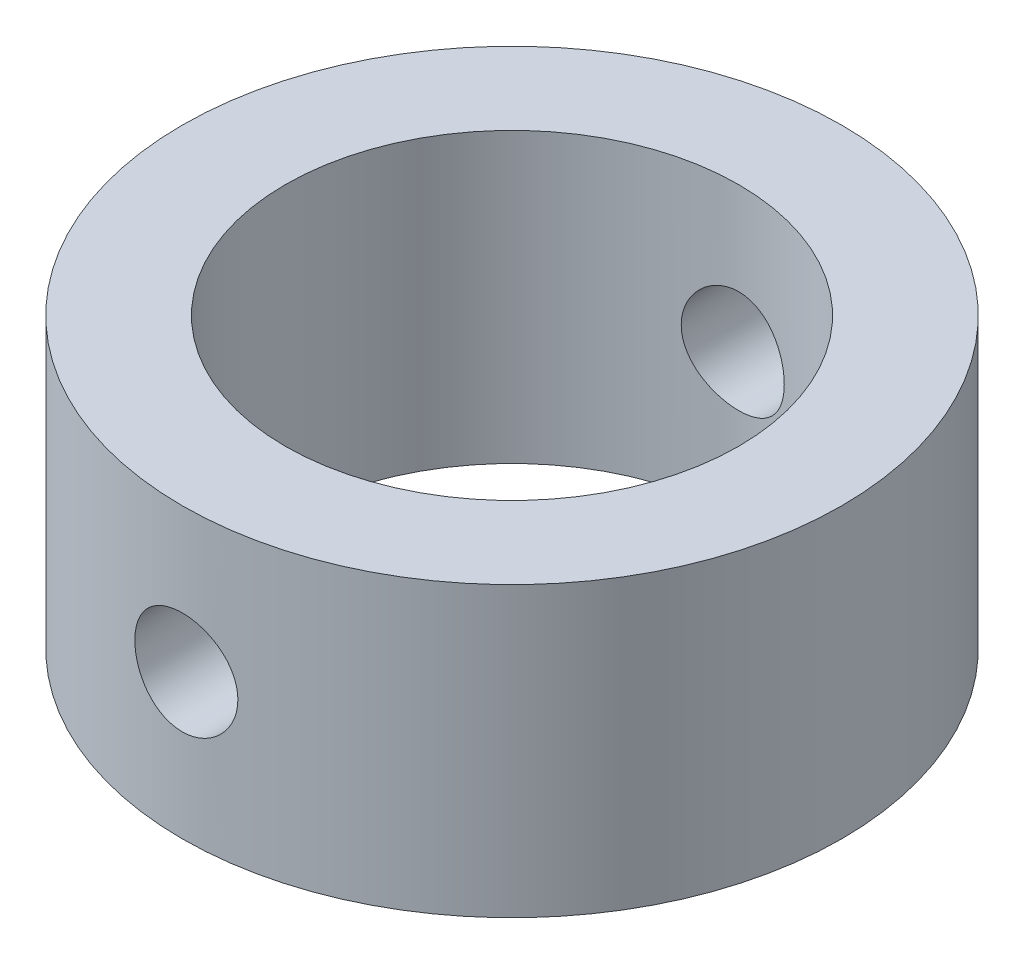
SolidWorks part; units mm, degrees
ref_plane "Front Plane" through (0, 0, 0) normal (0, 0, 1) x (1, 0, 0)
ref_plane "Top Plane" through (0, 0, 0) normal (0, 1, 0) x (1, 0, 0)
ref_plane "Right Plane" through (0, 0, 0) normal (1, 0, 0) x (0, 0, -1)
sketch "Sketch1" plane through (0, 0, 0) normal (0, 0, 1) x (1, 0, 0)
  line L0 (0, 0) -> (0, 14) construction
  line L2 (-16, 14) -> (-11, 14)
  line L3 (-16, 14) -> (-16, 0)
  line L4 (-16, 0) -> (-11, 0)
  line L5 (-11, 14) -> (-11, 0)
  dimension "D1" = 14
  dimension "D2" = 22
  dimension "D3" = 32
revolve "Revolve1" add sketch "Sketch1" angle 360 about L0
sketch "Sketch2" plane through (0, 0, 0) normal (0, 0, 1) x (1, 0, 0)
  line L0 (-16, 0) -> (16, 0) construction
  circle A0 centre (0, 7) radius 2.5
  point P4 (0, 0)
  dimension "D1" = 5
  dimension "D2" = 7
extrude "Cut-Extrude1" cut sketch "Sketch2" against normal through all both and the other way through all
